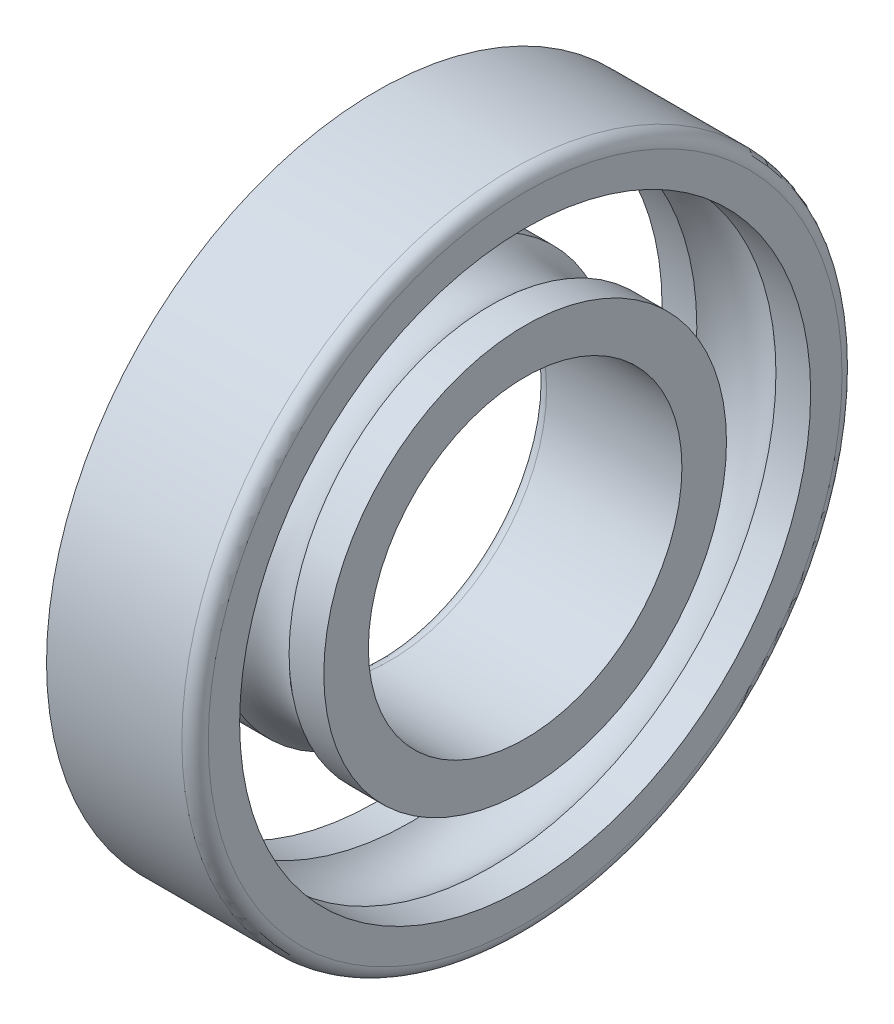
SolidWorks part; units mm, degrees
material "合金钢"
ref_plane "前视基准面" through (0, 0, 0) normal (0, 0, 1) x (1, 0, 0)
ref_plane "上视基准面" through (0, 0, 0) normal (0, 1, 0) x (1, 0, 0)
ref_plane "右视基准面" through (0, 0, 0) normal (1, 0, 0) x (0, 0, -1)
sketch "草图1" plane through (0, 0, 0) normal (0, 0, 1) x (1, 0, 0)
  line L0 (-49.6593, 0) -> (79.1925, 0) construction
  line L1 (11.987, 86.5) -> (22.5, 86.5)
  line L2 (-22.5, 100) -> (22.5, 100)
  line L3 (-22.5, 100) -> (-22.5, 86.5)
  line L4 (-22.5, 86.5) -> (-11.987, 86.5)
  line L5 (22.5, 100) -> (22.5, 86.5)
  line L6 (-22.5, 61) -> (-11.987, 61)
  line L7 (-22.5, 61) -> (-22.5, 47.5)
  line L8 (-22.5, 47.5) -> (22.5, 47.5)
  line L9 (22.5, 61) -> (22.5, 47.5)
  line L10 (11.987, 61) -> (22.5, 61)
  arc A0 (11.987, 86.5) -> (-11.987, 86.5) centre (0, 73.75) ccw
  arc A1 (-11.987, 61) -> (11.987, 61) centre (0, 73.75) ccw
  dimension "D5" = 17.5
  dimension "D1" = 86.5
  dimension "D2" = 22.5
  dimension "D3" = 22.5
  dimension "D4" = 100
  dimension "D6" = 26.25
  dimension "D7" = 47.5
  dimension "D8" = 61
  dimension "D9" = 22.5
  dimension "D10" = 22.5
  dimension "D11" = 73.75
revolve "旋转1" add sketch "草图1" angle 360 about L0
fillet "圆角1" radius 4 1 edges at (22.5, 0, 100)
fillet "圆角2" radius 4 1 edges at (-22.5, 0, 47.5)
